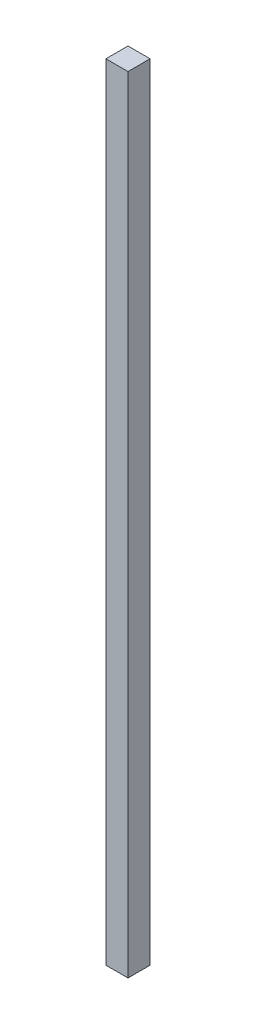
SolidWorks part; units mm, degrees
ref_plane "前视基准面" through (0, 0, 0) normal (0, 0, 1) x (1, 0, 0)
ref_plane "上视基准面" through (0, 0, 0) normal (0, 1, 0) x (1, 0, 0)
ref_plane "右视基准面" through (0, 0, 0) normal (1, 0, 0) x (0, 0, -1)
other "Configuration Table"
sketch "草图1" plane through (0, 0, 0) normal (0, 1, 0) x (1, 0, 0)
  line L1 (0, 0) -> (3.1, 0)
  line L2 (0, 0) -> (0, 3.1)
  line L3 (0, 3.1) -> (3.1, 3.1)
  line L4 (3.1, 0) -> (3.1, 3.1)
  dimension "D1" = 3.1
  dimension "D2" = 3.1
extrude "凸台-拉伸1" add sketch "草图1" along normal blind 110
